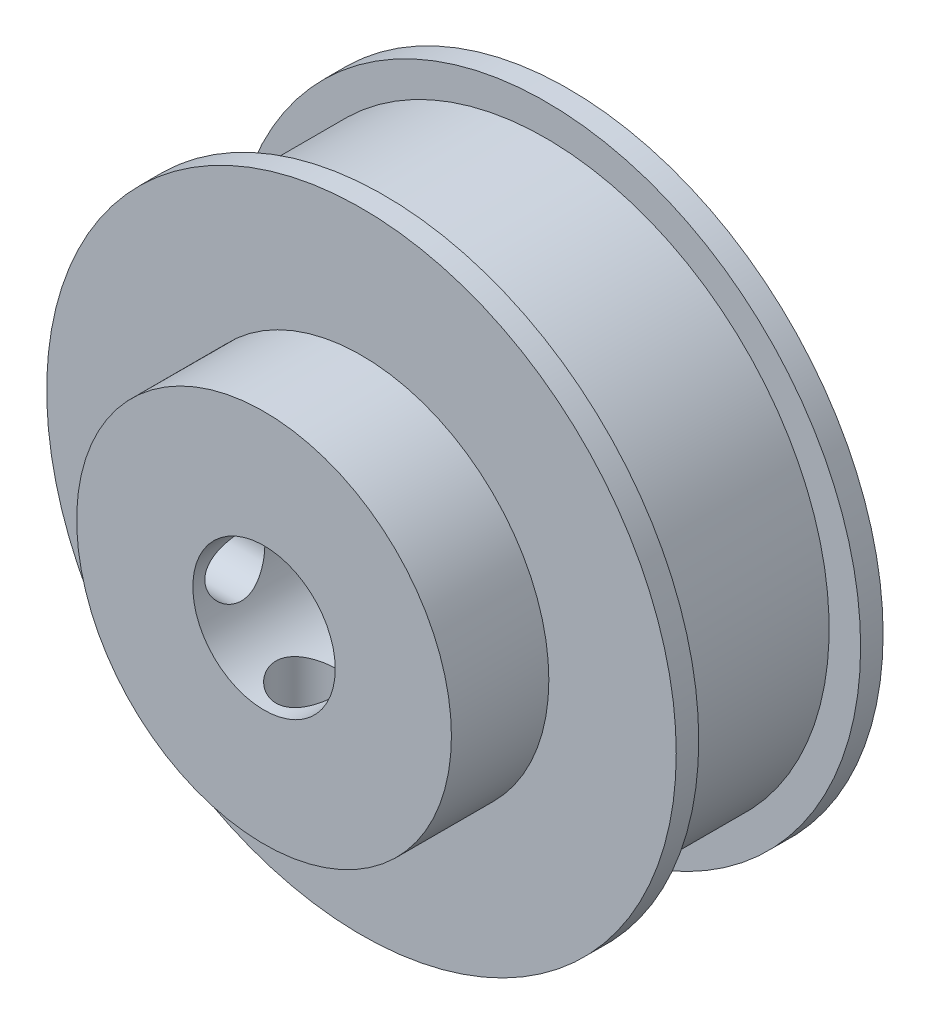
SolidWorks part; units mm, degrees
ref_plane "Alzado" through (0, 0, 0) normal (0, 0, 1) x (1, 0, 0)
ref_plane "Planta" through (0, 0, 0) normal (0, 1, 0) x (1, 0, 0)
ref_plane "Vista lateral" through (0, 0, 0) normal (1, 0, 0) x (0, 0, -1)
sketch "Croquis1" plane through (0, 0, 0) normal (0, 0, 1) x (1, 0, 0)
  circle A0 centre (0, 0) radius 21
  dimension "D1" = 42
extrude "Saliente-Extruir1" add sketch "Croquis1" along normal blind 1.5
sketch "Croquis2" plane through (0, 0, 1.5) normal (0, 0, 1) x (1, 0, 0)
  circle A0 centre (0, 0) radius 18.9
  dimension "D1" = 37.8
extrude "Saliente-Extruir2" add sketch "Croquis2" along normal blind 10.8
sketch "Croquis3" plane through (0, 0, 12.3) normal (0, 0, 1) x (1, 0, 0)
  circle A0 centre (0, 0) radius 21
  dimension "D1" = 42
extrude "Saliente-Extruir3" add sketch "Croquis3" along normal blind 1.5
sketch "Croquis8" plane through (0, 0, 13.8) normal (0, 0, 1) x (1, 0, 0)
  circle A0 centre (0, 0) radius 12.5
  dimension "D1" = 25
extrude "Saliente-Extruir5" add sketch "Croquis8" along normal blind 6.5
sketch "Croquis6" plane through (0, 0, 0) normal (0, 1, 0) x (1, 0, 0)
  line L0 (0, 0) -> (0, -17.5) construction
  circle A0 centre (0, -17.5) radius 2
  dimension "D2" = 4
  dimension "D1" = 17.5
extrude "Cortar-Extruir3" cut sketch "Croquis6" against normal through all
sketch "Croquis5" plane through (0, 0, 0) normal (1, 0, 0) x (0, 0, -1)
  line L0 (0, 0) -> (-17.5, 0) construction
  circle A0 centre (-17.5, 0) radius 2
  dimension "D2" = 4
  dimension "D1" = 17.5
extrude "Cortar-Extruir2" cut sketch "Croquis5" against normal through all
sketch "Croquis4" plane through (0, 0, 20.3) normal (0, 0, 1) x (1, 0, 0)
  circle A0 centre (0, 0) radius 4.75
  dimension "D1" = 9.5
extrude "Cortar-Extruir1" cut sketch "Croquis4" against normal through all
